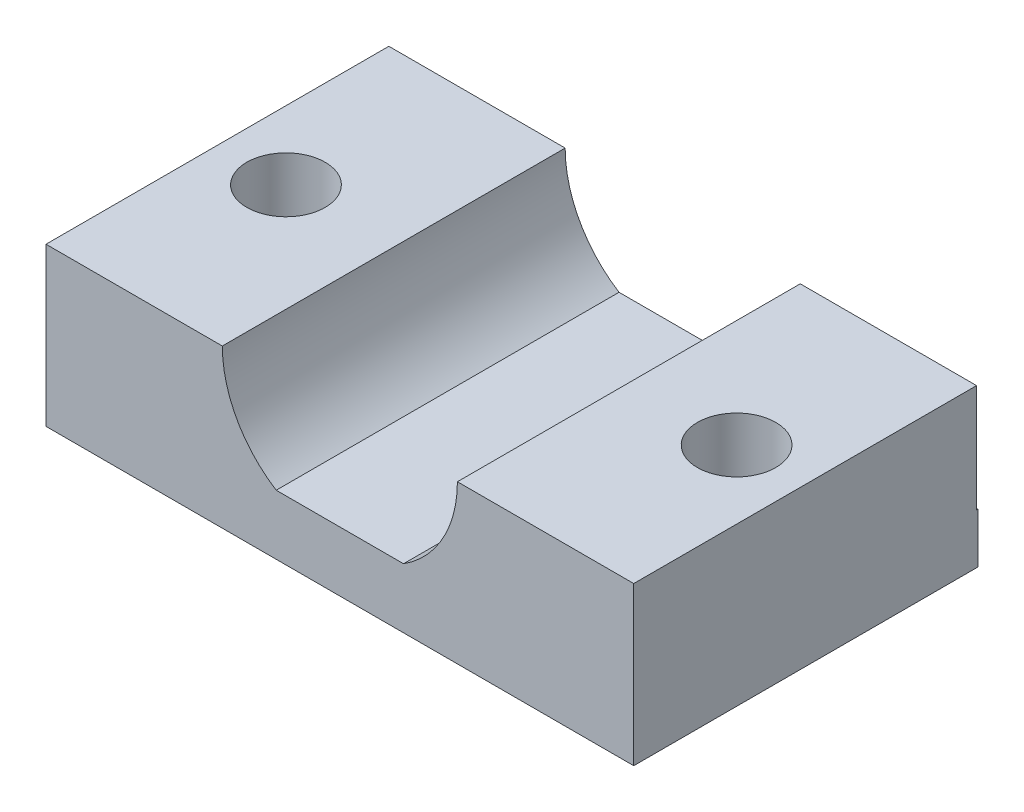
SolidWorks part; units mm, degrees
ref_plane "前基準面" through (0, 0, 0) normal (0, 0, 1) x (1, 0, 0)
ref_plane "上基準面" through (0, 0, 0) normal (0, 1, 0) x (1, 0, 0)
ref_plane "右基準面" through (0, 0, 0) normal (1, 0, 0) x (0, 0, -1)
sketch "草圖2" plane through (0, 0, 0) normal (1, 0, 0) x (0, 0, -1)
  line L1 (0, 4) -> (50, 4)
  line L2 (0, 4) -> (0, 0)
  line L3 (0, 0) -> (50, 0)
  line L4 (50, 4) -> (50, 0)
  dimension "D1" = 4
  dimension "D2" = 50
extrude "填料-伸長2" add sketch "草圖2" along normal mid plane 45
sketch "草圖15" plane through (0, 4, 0) normal (0, 1, 0) x (1, 0, 0)
  line L1 (22.5, 50) -> (22.5, 0) construction
  circle A0 centre (17.5, 39.2) radius 1.4
  circle A1 centre (17.5, 24.2) radius 1.4
  dimension "D1" = 2.8
  dimension "D2" = 15
  dimension "D4" = 5
extrude "填料-伸長8" add sketch "草圖15" along normal blind 5
sketch "草圖3" plane through (0, 4, 0) normal (0, 1, 0) x (1, 0, 0)
  line L1 (-15, 20) -> (15, 20)
  line L2 (-15, 20) -> (-15, 0)
  line L3 (-15, 0) -> (15, 0)
  line L4 (15, 20) -> (15, 0)
  dimension "D1" = 20
  dimension "D2" = 30
extrude "填料-伸長4" add sketch "草圖3" along normal blind 20
sketch "草圖16" plane through (0, 0, 0) normal (0, 0, -1) x (-1, 0, 0)
  line L0 (-15, 24) -> (-15, 36)
  line L1 (-15, 24) -> (15, 24) construction
  line L2 (-15, 36) -> (-6, 36)
  line L3 (-3.25, 31) -> (3.25, 31)
  line L4 (0, -1000) -> (0, 49000) construction
  line L5 (-15, 24) -> (15, 24)
  line L6 (15, 24) -> (15, 36)
  line L7 (15, 36) -> (6, 36)
  line L10 (-3.25, 31) -> (3.25, 31) construction
  arc A0 (-6, 36) -> (-3.25, 31) centre (-0.0795, 36) ccw
  arc A1 (6, 36) -> (3.25, 31) centre (0.0795, 36) cw
  arc A2 (-5.9149, 35) -> (-3.25, 31) centre (-0.0795, 36) ccw construction
  point P13 (0, 24)
  point P17 (0, 31)
  dimension "D2" = 30
  dimension "D3" = 5
extrude "填料-伸長9" add sketch "草圖16" along normal blind 17.5
sketch "草圖18" plane through (0, 0, 0) normal (1, 0, 0) x (0, 0, -1)
  line L0 (17.5, 24) -> (28.5, 24)
  line L1 (28.5, 24) -> (28.5, 42.7488)
  line L2 (28.5, 42.7488) -> (27, 42.7488)
  line L3 (27, 42.7488) -> (27, 30.5)
  line L4 (27, 30.5) -> (17.5, 30.5)
  line L5 (17.5, 36) -> (17.5, 24) construction
  line L6 (17.5, 30.5) -> (17.5, 24)
  line L8 (17.5, 24) -> (20, 24) construction
  dimension "D1" = 1.5
  dimension "D2" = 9.5
  dimension "D3" = 6.5
extrude "填料-伸長10" add sketch "草圖18" along normal mid plane 30
sketch "草圖19" plane through (0, 0, -28.5) normal (0, 0, -1) x (-1, 0, 0)
  circle A0 centre (0, 36) radius 2.1
  dimension "D1" = 4.2
extrude "除料-伸長1" cut sketch "草圖19" against normal up to next
sketch "草圖20" plane through (0, 36, 0) normal (0, 1, 0) x (1, 0, 0)
  circle A0 centre (-11.5, 8.75) radius 2
  circle A1 centre (11.5, 8.75) radius 2
extrude "除料-伸長2" cut sketch "草圖20" against normal blind 10
sketch "草圖21" plane through (0, 0, 0) normal (1, 0, 0) x (0, 0, -1)
  line L0 (0, 0) -> (0, 27.9457)
  line L1 (0, 27.9457) -> (17.5728, 27.9457)
  line L2 (17.5728, 27.9457) -> (17.5728, 46.3994)
  line L3 (17.5728, 46.3994) -> (61.4614, 46.3994)
  line L4 (61.4614, 46.3994) -> (61.4614, 0)
  line L5 (61.4614, 0) -> (0, 0)
extrude "除料-伸長3" cut sketch "草圖21" against normal through all both and the other way through all
equation "\"ˋ0\"=50"
